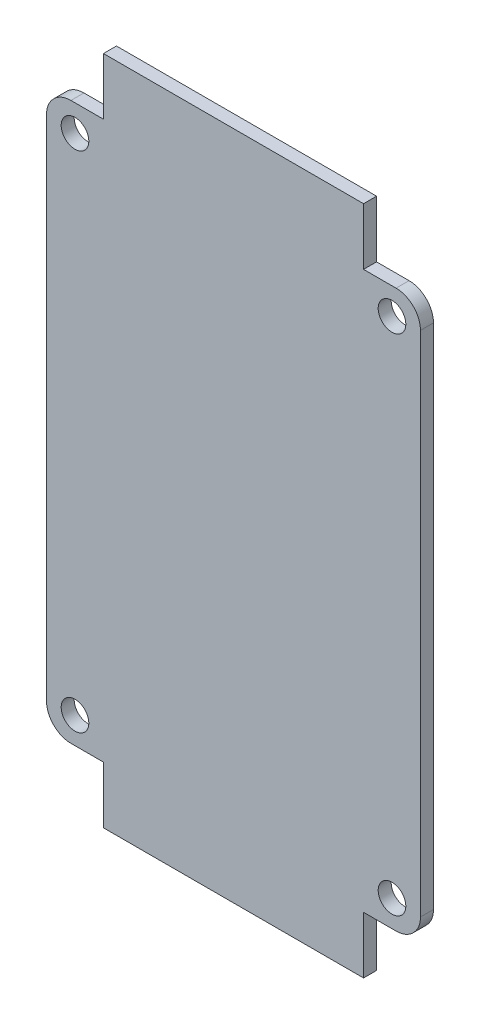
SolidWorks part; units mm, degrees
ref_plane "Спереди" through (0, 0, 0) normal (0, 0, 1) x (1, 0, 0)
ref_plane "Сверху" through (0, 0, 0) normal (0, 1, 0) x (1, 0, 0)
ref_plane "Справа" through (0, 0, 0) normal (1, 0, 0) x (0, 0, -1)
sketch "Эскиз1" plane through (0, 0, 0) normal (0, 0, 1) x (1, 0, 0)
  line L0 (-16, 34.25) -> (-16, 41.25)
  line L1 (-20, -34.25) -> (-16, -34.25)
  line L2 (-23, -31.25) -> (-23, 31.25)
  line L3 (-20, 34.25) -> (-16, 34.25)
  line L4 (23, -31.25) -> (23, 31.25)
  line L5 (-23, -34.25) -> (23, 34.25) construction
  line L6 (-23, 34.25) -> (23, -34.25) construction
  line L7 (24.125, 41.25) -> (-24.125, 41.25) construction
  line L8 (-16, 41.25) -> (16, 41.25)
  line L9 (16, 41.25) -> (16, 34.25)
  line L10 (16, 34.25) -> (20, 34.25)
  line L11 (-16, -34.25) -> (-16, -41.25)
  line L12 (24.125, -41.25) -> (-24.125, -41.25) construction
  line L13 (-16, -41.25) -> (16, -41.25)
  line L14 (16, -41.25) -> (16, -34.25)
  line L15 (16, -34.25) -> (20, -34.25)
  arc A0 (-20, -34.25) -> (-23, -31.25) centre (-20, -31.25) cw
  arc A1 (20, -34.25) -> (23, -31.25) centre (20, -31.25) ccw
  arc A2 (20, 34.25) -> (23, 31.25) centre (20, 31.25) cw
  arc A3 (-23, 31.25) -> (-20, 34.25) centre (-20, 31.25) cw
  point P0 (0, 0)
  point P16 (0, 41.25)
  point P19 (0, -41.25)
  dimension "D4" = 3
  dimension "D1" = 32
  dimension "D2" = 68.5
  dimension "D3" = 46
extrude "Бобышка-Вытянуть1" add sketch "Эскиз1" along normal blind 1.6
hole_wizard "Отверстие с зазором M31" positions "Эскиз3" profile "Эскиз4" hole size "M3" standard "DIN"
sketch "Эскиз3" plane through (0, 0, 1.6) normal (0, 0, 1) x (1, 0, 0)
  point P0 (-19.5, 31)
  point P3 (19.5, 31)
  point P6 (19.5, -31)
  point P9 (-19.5, -31)
sketch "Эскиз4" plane through (-19.5, 31, 1.6) normal (1, 0, 0) x (0, -1, 0)
  line L0 (0, 0) -> (0, 11.0215)
  line L1 (0, 11.0215) -> (1.7, 10)
  line L2 (1.7, 10) -> (1.7, 0)
  line L5 (1.7, 0) -> (0, 0)
  line L10 (0, 11.0215) -> (-1.7, 10) construction
  line L11 (0, -6.35) -> (0, 107.95) construction
  dimension "Диаметр отверстия" = 3.4
  dimension "Глубина отверстия" = 10
  dimension "Угол заточки сверла" = 118
